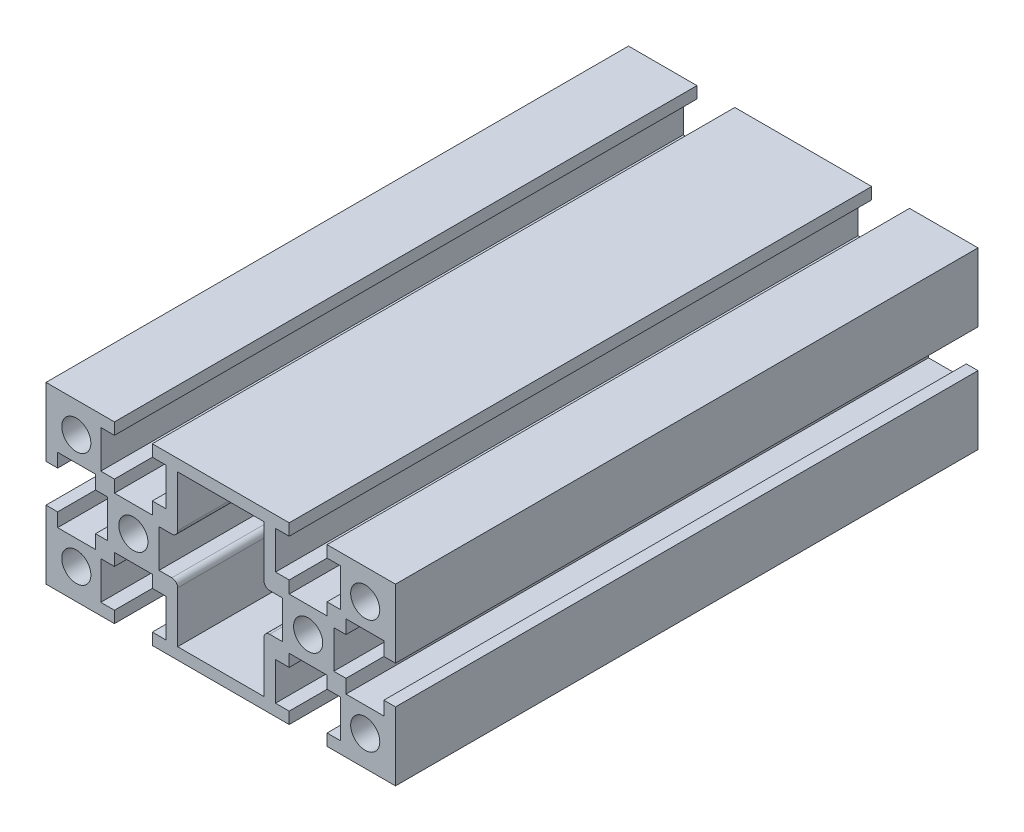
SolidWorks part; units mm, degrees
ref_plane "前视基准面" through (0, 0, 0) normal (0, 0, 1) x (1, 0, 0)
ref_plane "上视基准面" through (0, 0, 0) normal (0, 1, 0) x (1, 0, 0)
ref_plane "右视基准面" through (0, 0, 0) normal (1, 0, 0) x (0, 0, -1)
sketch "草图1" plane through (0, 0, 0) normal (0, 0, 1) x (1, 0, 0)
  line B0 (-15, 15) -> (-3.25, 15)
  line B1 (3.25, 15) -> (26.75, 15)
  line B2 (33.25, 15) -> (45, 15)
  line B3 (-15, -15) -> (-3.25, -15)
  line B4 (3.25, -15) -> (26.75, -15)
  line B5 (33.25, -15) -> (45, -15)
  line B6 (-15, -15) -> (-15, -3.25)
  line B7 (-15, 3.25) -> (-15, 15)
  line B8 (-4.4, -3.25) -> (-4.4, 3.25)
  line B9 (-6.5, -5.6) -> (-6.5, -3.25)
  line B10 (-6.5, 3.25) -> (-6.5, 5.6)
  line B11 (-13, -5.6) -> (-13, -3.25)
  line B12 (-13, 3.25) -> (-13, 5.6)
  line B13 (-13, 5.6) -> (-6.5, 5.6)
  line B14 (-6.5, -5.6) -> (-13, -5.6)
  line B15 (-15, -3.25) -> (-13, -3.25)
  line B16 (-15, 3.25) -> (-13, 3.25)
  line B17 (-6.5, -3.25) -> (-4.4, -3.25)
  line B18 (-6.5, 3.25) -> (-4.4, 3.25)
  line B19 (3.25, -4.4) -> (-3.25, -4.4)
  line B20 (5.6, -6.5) -> (3.25, -6.5)
  line B21 (-3.25, -6.5) -> (-5.6, -6.5)
  line B22 (5.6, -13) -> (3.25, -13)
  line B23 (-3.25, -13) -> (-5.6, -13)
  line B24 (-5.6, -13) -> (-5.6, -6.5)
  line B25 (5.6, -6.5) -> (5.6, -13)
  line B26 (3.25, -15) -> (3.25, -13)
  line B27 (-3.25, -15) -> (-3.25, -13)
  line B28 (3.25, -6.5) -> (3.25, -4.4)
  line B29 (-3.25, -6.5) -> (-3.25, -4.4)
  line B30 (-3.25, 4.4) -> (3.25, 4.4)
  line B31 (-5.6, 6.5) -> (-3.25, 6.5)
  line B32 (3.25, 6.5) -> (5.6, 6.5)
  line B33 (-5.6, 13) -> (-3.25, 13)
  line B34 (3.25, 13) -> (5.6, 13)
  line B35 (5.6, 13) -> (5.6, 6.5)
  line B36 (7.6, 13) -> (7.6, 4.25)
  line B37 (-5.6, 6.5) -> (-5.6, 13)
  line B38 (-3.25, 15) -> (-3.25, 13)
  line B39 (3.25, 15) -> (3.25, 13)
  line B40 (-3.25, 6.5) -> (-3.25, 4.4)
  line B41 (3.25, 6.5) -> (3.25, 4.4)
  line B42 (45, 3.25) -> (45, 15)
  line B43 (34.4, -3.25) -> (34.4, 3.25)
  line B44 (36.5, -5.6) -> (36.5, -3.25)
  line B45 (36.5, 3.25) -> (36.5, 5.6)
  line B46 (43, -5.6) -> (43, -3.25)
  line B47 (43, 3.25) -> (43, 5.6)
  line B48 (43, 5.6) -> (36.5, 5.6)
  line B49 (36.5, -5.6) -> (43, -5.6)
  line B50 (45, -3.25) -> (43, -3.25)
  line B51 (45, 3.25) -> (43, 3.25)
  line B52 (36.5, -3.25) -> (34.4, -3.25)
  line B53 (36.5, 3.25) -> (34.4, 3.25)
  line B54 (26.75, -4.4) -> (33.25, -4.4)
  line B55 (24.4, -6.5) -> (26.75, -6.5)
  line B56 (33.25, -6.5) -> (35.6, -6.5)
  line B57 (24.4, -13) -> (26.75, -13)
  line B58 (33.25, -13) -> (35.6, -13)
  line B59 (35.6, -13) -> (35.6, -6.5)
  line B60 (24.4, -6.5) -> (24.4, -13)
  line B61 (26.75, -15) -> (26.75, -13)
  line B62 (33.25, -15) -> (33.25, -13)
  line B63 (26.75, -6.5) -> (26.75, -4.4)
  line B64 (33.25, -6.5) -> (33.25, -4.4)
  line B65 (33.25, 4.4) -> (26.75, 4.4)
  line B66 (35.6, 6.5) -> (33.25, 6.5)
  line B67 (26.75, 6.5) -> (24.4, 6.5)
  line B68 (35.6, 13) -> (33.25, 13)
  line B69 (26.75, 13) -> (24.4, 13)
  line B70 (24.4, 13) -> (24.4, 6.5)
  line B71 (22.4, 13) -> (22.4, 4.25)
  line B72 (35.6, 6.5) -> (35.6, 13)
  line B73 (33.25, 15) -> (33.25, 13)
  line B74 (26.75, 15) -> (26.75, 13)
  line B75 (33.25, 6.5) -> (33.25, 4.4)
  line B76 (26.75, 6.5) -> (26.75, 4.4)
  line B77 (45, -3.25) -> (45, -15)
  line B78 (4.4, -3.25) -> (4.4, 3.25)
  line B79 (6.6, 3.25) -> (4.4, 3.25)
  line B80 (22.4, 13) -> (7.6, 13)
  line B81 (7.6, -13) -> (7.6, -4.25)
  line B82 (22.4, -13) -> (22.4, -4.25)
  line B83 (6.6, -3.25) -> (4.4, -3.25)
  line B84 (22.4, -13) -> (7.6, -13)
  line B85 (25.6, -3.25) -> (25.6, 3.25)
  line B86 (23.4, 3.25) -> (25.6, 3.25)
  line B87 (23.4, -3.25) -> (25.6, -3.25)
  circle B88 centre (0, 0) radius 2.5
  circle B89 centre (30, 0) radius 2.5
  arc B90 (6.6, 3.25) -> (7.6, 4.25) centre (6.6, 4.25) ccw
  arc B91 (7.6, -4.25) -> (6.6, -3.25) centre (6.6, -4.25) ccw
  arc B92 (22.4, 4.25) -> (23.4, 3.25) centre (23.4, 4.25) ccw
  arc B93 (23.4, -3.25) -> (22.4, -4.25) centre (23.4, -4.25) ccw
  circle B94 centre (39.8, 9.8) radius 2.5
  circle B95 centre (39.8, -9.8) radius 2.5
  circle B96 centre (-9.8, 9.8) radius 2.5
  circle B97 centre (-9.8, -9.8) radius 2.5
sketch_block_instance "A$C7D535D44-1"
sketch_block "A$C7D535D44"
extrude "凸台-拉伸1" add sketch "草图1" along normal blind 100
